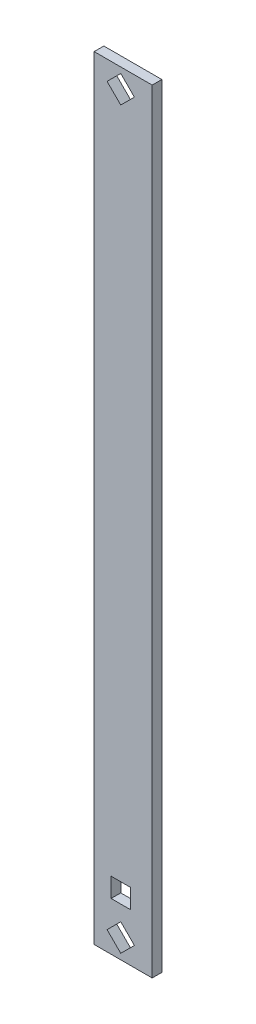
SolidWorks part; units mm, degrees
ref_plane "Top" through (0, 0, 0) normal (0, 0, 1) x (1, 0, 0)
ref_plane "Front" through (0, 0, 0) normal (0, 1, 0) x (1, 0, 0)
ref_plane "Right" through (0, 0, 0) normal (1, 0, 0) x (0, 0, -1)
sketch "Profile Sketch" plane through (-13.8341, 0, -105.7567) normal (0, 1, 0) x (-1, 0, 0)
  line L1 (-3, 0) -> (3, 0)
  line L2 (-3, 0) -> (-3, 1)
  line L3 (-3, 1) -> (3, 1)
  line L4 (3, 0) -> (3, 1)
  line L5 (0, 1) -> (0, 0) construction
  line L6 (-3, 0.5) -> (3, 0.5) construction
  point P128 (0, 0.5)
  dimension "Height" = 1
  dimension "Width" = 6
extrude "Profile Extrude" add sketch "Profile Sketch" along normal blind 80
sketch "Fiducial Sketch" plane through (0, 0, -104.7567) normal (0, 0, 1) x (1, 0, 0)
  line L0 (-14.0841, 2) -> (-12.6698, 2) construction
  line L1 (-12.6698, 2) -> (-14.0841, 3.4142)
  line L2 (-14.0841, 3.4142) -> (-15.4983, 2)
  line L3 (-15.4983, 2) -> (-14.0841, 0.5858)
  line L4 (-14.0841, 0.5858) -> (-12.6698, 2)
  line L9 (-14.0841, 2) -> (-14.0841, 0) construction
  line L10 (-16.8341, 0) -> (-10.8341, 0) construction
  line L17 (-16.8341, 80) -> (-16.8341, 0) construction
  circle A0 centre (-14.0841, 2) radius 1.4142 construction
  point P85 (-14.0841, 4)
  dimension "D1" = 2.8284
  dimension "Fiducial Y Spacing" = 2
  dimension "Fiducial X Position" = 2.75
extrude "Fiducial Cut" cut sketch "Fiducial Sketch" against normal through all
ref_plane "Mid Plane" through (0, 40, 0) normal (0, -1, 0) x (-1, 0, 0)
mirror "Fiducial Mirror" about plane through (0, 40, 0) normal (0, -1, 0) of "Fiducial Cut"
sketch "Fiducial 1 Indicator Sketch" plane through (0, 0, -104.7567) normal (0, 0, 1) x (1, 0, 0)
  line L9 (-14.0841, 2) -> (-14.0841, 0) construction
  line L11 (-15.0841, 4) -> (-13.0841, 4) construction
  line L12 (-15.0841, 7) -> (-13.0841, 7)
  line L13 (-15.0841, 7) -> (-15.0841, 5)
  line L14 (-15.0841, 5) -> (-13.0841, 5)
  line L15 (-13.0841, 7) -> (-13.0841, 5)
  line L16 (-14.0841, 5) -> (-14.0841, 7) construction
  line L17 (-15.0841, 6) -> (-13.0841, 6) construction
  line L18 (-16.8341, 0) -> (-10.8341, 0) construction
  line L19 (-16.8341, 80) -> (-16.8341, 0) construction
  point P85 (-14.0841, 6)
  dimension "Fiducial X Position" = 2.75
  dimension "D2" = 2.8284
extrude "Indicator of Fiducial 1 Cut" cut sketch "Fiducial 1 Indicator Sketch" against normal through all
equation "\"D1@Fiducial Sketch\" = 2 * sqr ( 2 ) "
equation "\"D2@Fiducial 1 Indicator Sketch\" = 2 * sqr ( 2 ) "
